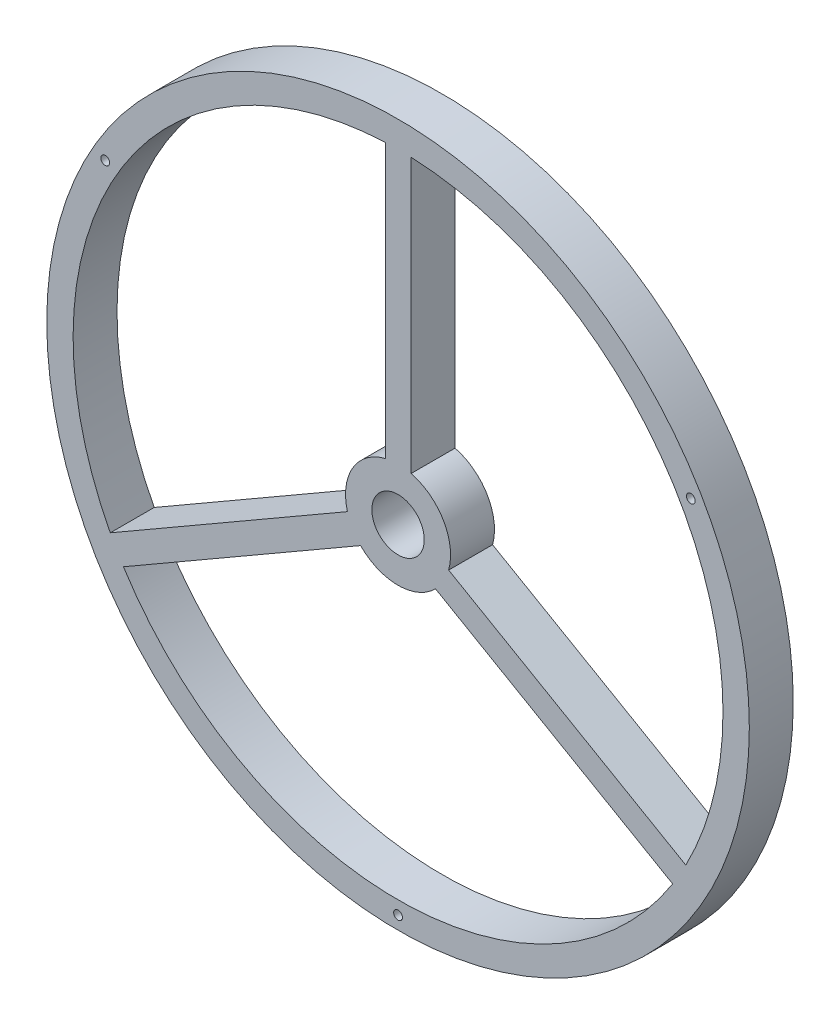
SolidWorks part; units mm, degrees
ref_plane "前视基准面" through (0, 0, 0) normal (0, 0, 1) x (1, 0, 0)
ref_plane "上视基准面" through (0, 0, 0) normal (0, 1, 0) x (1, 0, 0)
ref_plane "右视基准面" through (0, 0, 0) normal (1, 0, 0) x (0, 0, -1)
sketch "草图1" plane through (0, 0, 0) normal (0, 0, 1) x (1, 0, 0)
  line L0 (48.2965, 27.9249) -> (48.2965, 67.9249) construction
  line L1 (48.2965, 27.9249) -> (13.6555, 7.9249) construction
  line L2 (48.2965, 27.9249) -> (82.9375, 7.9249) construction
  line L3 (81.0732, 9.0013) -> (81.8232, 10.3003)
  line L7 (46.8483, 66.0915) -> (46.8483, 32.6388)
  line L11 (49.7879, 66.0915) -> (49.7879, 32.6388)
  line L12 (81.0732, 9.0013) -> (80.3232, 7.7022)
  line L13 (81.8232, 10.3003) -> (52.5654, 27.1923)
  line L14 (52.5654, 27.1923) -> (51.0654, 24.5942)
  line L15 (51.0654, 24.5942) -> (80.3232, 7.7022)
  line L16 (15.5198, 9.0013) -> (14.7698, 10.3003)
  line L17 (15.5198, 9.0013) -> (16.2698, 7.7022)
  line L18 (14.7698, 10.3003) -> (43.9274, 27.1345)
  line L19 (43.9274, 27.1345) -> (45.4274, 24.5364)
  line L20 (45.4274, 24.5364) -> (16.2698, 7.7022)
  line L21 (46.8483, 32.6388) -> (49.7879, 32.6388)
  line L22 (46.8483, 66.0915) -> (49.7879, 66.0915)
  circle A1 centre (48.2965, 27.9249) radius 2.9807
  circle A2 centre (48.2965, 27.9249) radius 5.9807
  circle A3 centre (48.2965, 27.9249) radius 40
  circle A4 centre (48.2965, 27.9249) radius 37
  point P10 (49.8633, 66.1573)
  dimension "D1" = 3
  dimension "D2" = 3
extrude "凸台-拉伸2" add sketch "草图1" along normal blind 5 contours A3 A4 L7 L22 L11 L13 L3 L12 L15 L20 L17 L16 L18 | L7 A2 L18 L19 L20 L15 L14 L13 L11 L21 A1 | L18 A4 L20 A2 | A4 L18 L16 L17 L20 | L15 A2 L13 L14 | L11 A2 L7 L21 | L18 A2 L20 L19 | L11 A4 L7 A2 | A4 L11 L22 L7 | A4 L15 L12 L3 L13 | L15 A4 L13 A2
sketch "草图2" plane through (0, 0, 5) normal (0, 0, 1) x (1, 0, 0)
  line L0 (48.2965, 27.9249) -> (14.9545, 47.1749)
  line L1 (48.2965, 27.9249) -> (81.6385, 47.1749)
  line L2 (48.2965, 27.9249) -> (48.2965, -10.5751)
  circle A0 centre (14.9545, 47.1749) radius 0.5
  circle A1 centre (81.6385, 47.1749) radius 0.5
  circle A2 centre (48.2965, -10.5751) radius 0.5
  point P8 (0, 0)
extrude "切除-拉伸1" cut sketch "草图2" against normal blind 5
